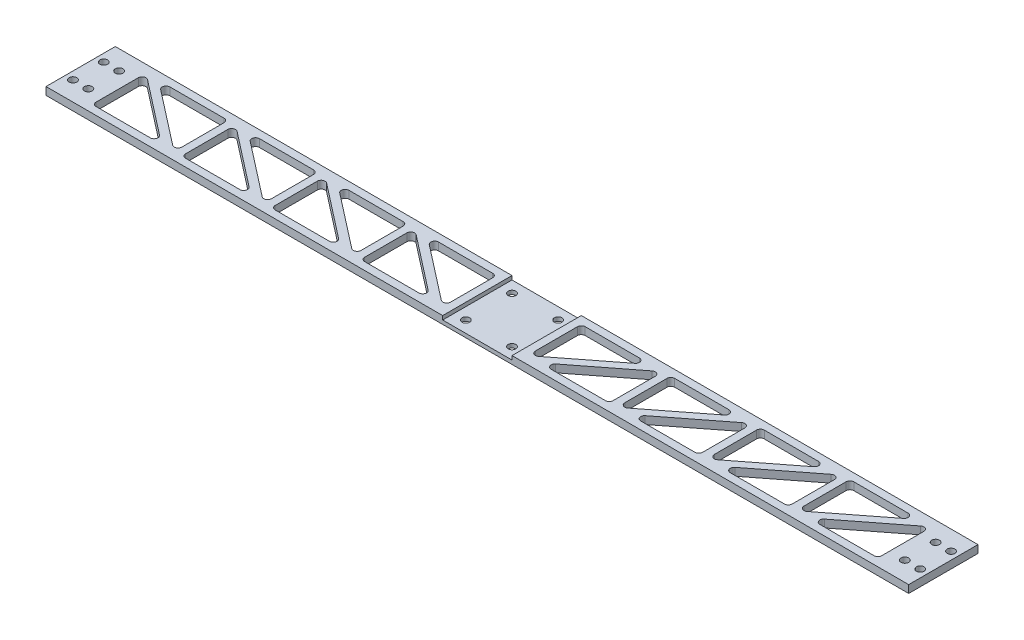
SolidWorks part; units mm, degrees
material "6061-T6 (SS)"
ref_plane "Front Plane" through (0, 0, 0) normal (0, 0, 1) x (1, 0, 0)
ref_plane "Top Plane" through (0, 0, 0) normal (0, 1, 0) x (1, 0, 0)
ref_plane "Right Plane" through (0, 0, 0) normal (1, 0, 0) x (0, 0, -1)
sketch "Sketch2" plane through (0, 0, 0) normal (1, 0, 0) x (0, 0, -1)
  line L1 (-28.575, 3.175) -> (28.575, 3.175)
  line L2 (-28.575, 3.175) -> (-28.575, -3.175)
  line L3 (-28.575, -3.175) -> (28.575, -3.175)
  line L4 (28.575, 3.175) -> (28.575, -3.175)
  line L5 (-28.575, 3.175) -> (28.575, -3.175) construction
  line L6 (-28.575, -3.175) -> (28.575, 3.175) construction
  point P0 (0, 0)
  dimension "D1" = 6.35
  dimension "D2" = 57.15
extrude "Boss-Extrude2" add sketch "Sketch2" along normal mid plane 711.2
hole_wizard "1/4 (0.25) Diameter Hole1" positions "Sketch4" profile "Sketch5" hole size "1/4" standard "ANSI Inch" end condition up to next
sketch "Sketch4" plane through (0, 3.175, 0) normal (0, 1, 0) x (1, 0, 0)
  line L1 (-349.25, -12.7) -> (-336.55, -12.7) construction
  line L2 (-349.25, -12.7) -> (-349.25, 12.7) construction
  line L3 (-349.25, 12.7) -> (-336.55, 12.7) construction
  line L4 (-336.55, -12.7) -> (-336.55, 12.7) construction
  line L5 (-355.6, 28.575) -> (-355.6, -28.575) construction
  line L6 (-355.6, 0) -> (355.6, 0) construction
  line L7 (355.6, 28.575) -> (355.6, -28.575) construction
  point P0 (-349.25, -12.7)
  point P2 (-349.25, 12.7)
  point P4 (-336.55, 12.7)
  point P6 (-336.55, -12.7)
  point P167 (-349.25, 0)
  dimension "D1" = 25.4
  dimension "D2" = 12.7
  dimension "D3" = 6.35
sketch "Sketch5" plane through (-349.25, 3.175, 12.7) normal (1, 0, 0) x (0, 0, 1)
  line L0 (0, 0) -> (0, 6.351)
  line L1 (0, 6.351) -> (3.175, 6.351)
  line L2 (3.175, 6.351) -> (3.175, 0)
  line L5 (3.175, 0) -> (0, 0)
  line L11 (0, -6.35) -> (0, 107.95) construction
  dimension "Thru Hole Dia." = 6.35
  dimension "Thru Hole Depth" = 6.351
sketch "Sketch6" plane through (0, 3.175, 0) normal (0, 1, 0) x (1, 0, 0)
  line L0 (-323.85, 22.225) -> (-323.85, -22.225)
  line L1 (-323.85, -22.225) -> (-266.7218, -22.225)
  line L2 (-266.7218, -22.225) -> (-323.85, 22.225)
  line L3 (-313.5094, 22.225) -> (-256.3813, -22.225)
  line L4 (-256.3813, -22.225) -> (-256.3813, 22.225)
  line L5 (-256.3813, 22.225) -> (-313.5094, 22.225)
  line L6 (-295.2859, 0) -> (-291.3865, 5.0117) construction
  line L7 (-330.2, 28.575) -> (-330.2, -28.575) construction
  line L8 (355.6, 28.575) -> (-355.6, 28.575) construction
  line L9 (355.6, -28.575) -> (-355.6, -28.575) construction
  line L10 (-323.85, 0) -> (-330.2, 0) construction
  line L11 (-250.0312, 22.225) -> (-250.0312, -22.225)
  line L12 (-250.0312, -22.225) -> (-192.9031, -22.225)
  line L13 (-192.9031, -22.225) -> (-250.0312, 22.225)
  line L14 (-239.6907, 22.225) -> (-182.5625, -22.225)
  line L15 (-182.5625, -22.225) -> (-182.5625, 22.225)
  line L16 (-182.5625, 22.225) -> (-239.6907, 22.225)
  line L17 (-221.4672, 0) -> (-217.5677, 5.0117) construction
  line L19 (-182.5625, 0) -> (-176.2125, 0) construction
  line L20 (-176.2125, 22.225) -> (-176.2125, -22.225)
  line L21 (-176.2125, -22.225) -> (-119.0843, -22.225)
  line L22 (-119.0843, -22.225) -> (-176.2125, 22.225)
  line L23 (-165.8719, 22.225) -> (-108.7438, -22.225)
  line L24 (-108.7438, -22.225) -> (-108.7438, 22.225)
  line L25 (-28.575, -28.575) -> (-28.575, 28.575) construction
  line L26 (-256.3813, 0) -> (-250.0312, 0) construction
  line L27 (-108.7438, 22.225) -> (-165.8719, 22.225)
  line L28 (28.575, 28.575) -> (28.575, -28.575) construction
  line L29 (0, -28.575) -> (0, 28.575) construction
  line L31 (-147.6484, 0) -> (-143.749, 5.0117) construction
  line L32 (-176.2125, 0) -> (-182.5625, 0) construction
  line L33 (-108.7438, 0) -> (-102.3938, 0) construction
  line L34 (-102.3937, 22.225) -> (-102.3937, -22.225)
  line L35 (-102.3937, -22.225) -> (-45.2656, -22.225)
  line L36 (-45.2656, -22.225) -> (-102.3937, 22.225)
  line L37 (-92.0532, 22.225) -> (-34.925, -22.225)
  line L38 (-34.925, -22.225) -> (-34.925, 22.225)
  line L39 (-34.925, 22.225) -> (-92.0532, 22.225)
  line L40 (-73.8297, 0) -> (-69.9302, 5.0117) construction
  line L41 (-102.3937, 0) -> (-108.7437, 0) construction
  line L42 (-34.925, 0) -> (-28.575, 0) construction
  line L45 (-250.0312, 0) -> (-256.3812, 0) construction
  circle A0 centre (-336.55, 12.7) radius 3.175 construction
  dimension "D1" = 6.35
  dimension "D2" = 6.35
  dimension "D4" = 6.35
  dimension "D5" = 28.575
  dimension "D7" = 28.575
  dimension "D3" = 4
extrude "Cut-Extrude1" cut sketch "Sketch6" against normal up to next
fillet "Fillet1" radius 3.175 24 edges at (-92.0532, 0, -22.225) (-34.925, 0, 22.225) (-34.925, 0, -22.225) (-102.3937, 0, 22.225) (-45.2656, 0, 22.225) (-102.3937, 0, -22.225) (-165.8719, 0, -22.225) (-108.7438, 0, 22.225) (-108.7438, 0, -22.225) (-119.0843, 0, 22.225) (-176.2125, 0, -22.225) (-176.2125, 0, 22.225) (-182.5625, 0, 22.225) (-182.5625, 0, -22.225) (-239.6907, 0, -22.225) (-192.9031, 0, 22.225) (-250.0312, 0, -22.225) (-250.0312, 0, 22.225) (-313.5094, 0, -22.225) (-256.3813, 0, -22.225) (-256.3813, 0, 22.225) (-266.7218, 0, 22.225) (-323.85, 0, 22.225) (-323.85, 0, -22.225)
mirror "Mirror1" about plane through (0, 0, 0) normal (1, 0, 0) of "Fillet1", "Cut-Extrude1", "1/4 (0.25) Diameter Hole1"
sketch "Sketch7" plane through (0, 3.175, 0) normal (0, 1, 0) x (1, 0, 0)
  line L0 (355.6, 28.575) -> (-355.6, 28.575) construction
  line L1 (-28.575, 28.575) -> (28.575, 28.575)
  line L2 (-28.575, 28.575) -> (-28.575, -28.575)
  line L3 (-28.575, -28.575) -> (28.575, -28.575)
  line L4 (28.575, 28.575) -> (28.575, -28.575)
  line L5 (355.6, -28.575) -> (-355.6, -28.575) construction
  line L6 (-28.575, 0) -> (28.575, 0) construction
  point P10 (0, 0)
extrude "Cut-Extrude2" cut sketch "Sketch7" against normal blind 3.175
hole_wizard "1/4 (0.25) Diameter Hole2" positions "Sketch10" profile "Sketch9" hole size "1/4" standard "ANSI Inch" end condition up to next
sketch "Sketch10" plane through (0, 0, 0) normal (0, 1, 0) x (1, 0, 0)
  line L1 (-19.05, 19.05) -> (19.05, 19.05) construction
  line L2 (-19.05, 19.05) -> (-19.05, -19.05) construction
  line L3 (-19.05, -19.05) -> (19.05, -19.05) construction
  line L4 (19.05, 19.05) -> (19.05, -19.05) construction
  line L5 (-19.05, 19.05) -> (19.05, -19.05) construction
  line L6 (-19.05, -19.05) -> (19.05, 19.05) construction
  point P2 (19.05, -19.05)
  point P87 (-19.05, 19.05)
  point P88 (-19.05, -19.05)
  point P89 (19.05, 19.05)
  dimension "D1" = 38.1
sketch "Sketch9" plane through (19.05, 0, 19.05) normal (1, 0, 0) x (0, 0, 1)
  line L0 (0, 0) -> (0, 3.175)
  line L1 (0, 3.175) -> (3.175, 3.175)
  line L2 (3.175, 3.175) -> (3.175, 0)
  line L5 (3.175, 0) -> (0, 0)
  line L11 (0, -6.35) -> (0, 107.95) construction
  dimension "Thru Hole Dia." = 6.35
  dimension "Thru Hole Depth" = 3.175
